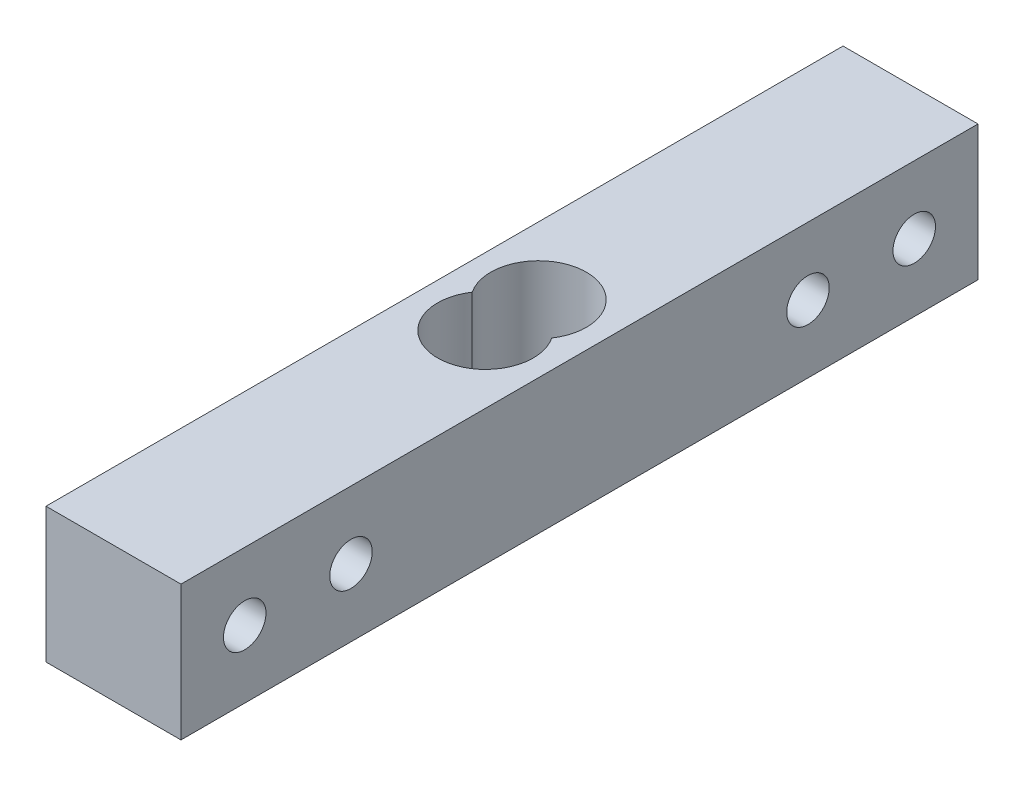
SolidWorks part; units mm, degrees
material "1060 Alloy"
ref_plane "Front Plane" through (0, 0, 0) normal (0, 0, 1) x (1, 0, 0)
ref_plane "Top Plane" through (0, 0, 0) normal (0, 1, 0) x (1, 0, 0)
ref_plane "Right Plane" through (0, 0, 0) normal (1, 0, 0) x (0, 0, -1)
sketch "Sketch1" plane through (0, 0, 0) normal (0, 0, 1) x (1, 0, 0)
  line L1 (-6.35, -6.35) -> (6.35, -6.35)
  line L2 (-6.35, -6.35) -> (-6.35, 6.35)
  line L3 (-6.35, 6.35) -> (6.35, 6.35)
  line L4 (6.35, -6.35) -> (6.35, 6.35)
  line L5 (-6.35, -6.35) -> (6.35, 6.35) construction
  line L6 (-6.35, 6.35) -> (6.35, -6.35) construction
  point P0 (0, 0)
  dimension "D1" = 12.7
  dimension "D2" = 12.7
extrude "Boss-Extrude1" add sketch "Sketch1" along normal mid plane 75
sketch "Sketch2" plane through (6.35, 0, 0) normal (1, 0, 0) x (0, 0, -1)
  line L0 (-31.5, 0) -> (31.5, 0) construction
  circle A0 centre (-31.5, 0) radius 2
  circle A1 centre (-21.5, 0) radius 2
  circle A2 centre (21.5, 0) radius 2
  circle A3 centre (31.5, 0) radius 2
  dimension "D5" = 4
  dimension "D6" = 4
  dimension "D7" = 4
  dimension "D8" = 4
  dimension "D1" = 10
  dimension "D2" = 10
  dimension "D3" = 43
  dimension "D4" = 21.5
extrude "Cut-Extrude1" cut sketch "Sketch2" against normal blind 80
sketch "Sketch3" plane through (0, -6.35, 0) normal (0, -1, 0) x (1, 0, 0)
  arc A0 (3.7417, 0) -> (-3.7417, 0) centre (0, 2.5) ccw
  arc A1 (-3.7417, 0) -> (3.7417, 0) centre (0, -2.5) ccw
  dimension "D1" = 9
  dimension "D2" = 9
  dimension "D3" = 2.5
  dimension "D4" = 2.5
extrude "Cut-Extrude2" cut sketch "Sketch3" against normal blind 80
equation "\"D4@Sketch2\"=\"D3@Sketch2\"/2"
